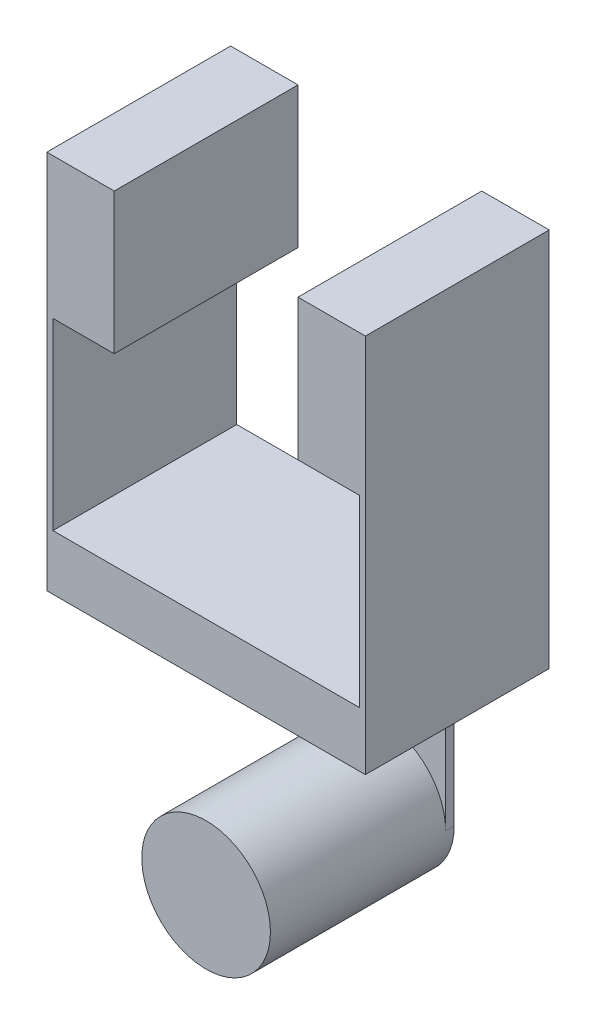
SolidWorks part; units mm, degrees
ref_plane "Front Plane" through (0, 0, 0) normal (0, 0, 1) x (1, 0, 0)
ref_plane "Top Plane" through (0, 0, 0) normal (0, 1, 0) x (1, 0, 0)
ref_plane "Right Plane" through (0, 0, 0) normal (1, 0, 0) x (0, 0, -1)
sketch "Sketch1" plane through (0, 0, 0) normal (0, 0, 1) x (1, 0, 0)
  circle A0 centre (0, 0) radius 13.335
  dimension "D1" = 26.67
extrude "FeatureA" add sketch "Sketch1" against normal blind 38.1 contours A0
ref_plane "Plane1" through (0, 0, -38.1) normal (0, 0, -1) x (-1, 0, 0)
sketch "Sketch2" plane through (0, 0, -38.1) normal (0, 0, -1) x (-1, 0, 0)
  line L0 (-13.335, 0) -> (13.335, 0)
  line L1 (13.335, 0) -> (13.335, 38.1)
  line L2 (13.335, 38.1) -> (-13.335, 38.1)
  line L3 (-13.335, 38.1) -> (-13.335, 0)
  circle A0 centre (0, 0) radius 13.335 construction
  dimension "D1" = 38.1
extrude "FeatureB" add sketch "Sketch2" against normal blind 1.778 contours L2 L3 L0 L1
ref_plane "Plane2" through (0, 38.1, 0) normal (0, 1, 0) x (1, 0, 0)
sketch "Sketch3" plane through (0, 38.1, 0) normal (0, 1, 0) x (1, 0, 0)
  line L0 (0, 38.1) -> (-33.02, 38.1)
  line L1 (14.6685, 38.1) -> (-14.6685, 38.1) construction
  line L2 (-33.02, 38.1) -> (-33.02, 0)
  line L3 (-33.02, 0) -> (33.02, 0)
  line L4 (33.02, 0) -> (33.02, 38.1)
  line L5 (33.02, 38.1) -> (0, 38.1)
  line L6 (33.02, 19.05) -> (-33.02, 19.05) construction
  line L9 (0, 38.1) -> (0, 0) construction
  dimension "D1" = 66.04
  dimension "D2" = 38.1
extrude "FeatureC" add sketch "Sketch3" along normal blind 11.43
sketch "Sketch4" plane through (0, 49.53, 0) normal (0, 1, 0) x (1, 0, 0)
  line L0 (14.6685, 38.1) -> (-14.6685, 38.1) construction
  line L1 (33.02, 0) -> (31.75, 0)
  line L2 (33.02, 0) -> (33.02, 38.1)
  line L3 (33.02, 38.1) -> (31.75, 38.1)
  line L4 (31.75, 0) -> (31.75, 38.1)
  line L5 (0, 38.1) -> (0, 0) construction
  line L6 (33.02, 38.1) -> (-33.02, 38.1) construction
  line L7 (-33.02, 0) -> (33.02, 0) construction
  line L8 (-33.02, 38.1) -> (-31.75, 38.1)
  line L9 (-31.75, 0) -> (-31.75, 38.1)
  line L10 (-33.02, 0) -> (-31.75, 0)
  line L11 (-33.02, 0) -> (-33.02, 38.1)
  dimension "D1" = 1.27
extrude "FeatureD" add sketch "Sketch4" along normal blind 38.1
sketch "Sketch7" plane through (0, 87.63, 0) normal (0, 1, 0) x (1, 0, 0)
  line L0 (14.6685, 38.1) -> (-14.6685, 38.1) construction
  line L1 (33.02, 0) -> (19.05, 0)
  line L2 (33.02, 0) -> (33.02, 38.1)
  line L3 (33.02, 38.1) -> (19.05, 38.1)
  line L4 (19.05, 0) -> (19.05, 38.1)
  line L5 (31.75, 38.1) -> (31.75, 0) construction
  line L6 (0, 0) -> (0, 41.6455) construction
  line L7 (-33.02, 38.1) -> (-19.05, 38.1)
  line L8 (-19.05, 0) -> (-19.05, 38.1)
  line L9 (-33.02, 0) -> (-19.05, 0)
  line L10 (-33.02, 0) -> (-33.02, 38.1)
  dimension "D1" = 12.7
extrude "Boss-Extrude5" add sketch "Sketch7" along normal blind 29.21
ref_plane "Plane3" through (0, 87.63, 0) normal (0, 1, 0) x (1, 0, 0)
equation "\"La\"= 1.5"
equation "\"Da\"= 1.05"
equation "\"Wb\"= \"La\""
equation "\"Lb\"= \"La\""
equation "\"tb\"= 0.07"
equation "\"bc\"= 0.498 + 0.9992 * 2"
equation "\"Lc\"= \"La\""
equation "\"hc\"= 0.45"
equation "\"hd\"= 1.499"
equation "\"Ld\"= \"La\""
equation "\"td\"= 0.05"
equation "\"be\"= 0.498"
equation "\"Le\"= \"La\""
equation "\"he\"= 1.15"
equation "\"E\"= 29 * 10 ^ 6"
equation "\"Sy\"= 36000"
equation "\"deflection\"= 0.005"
